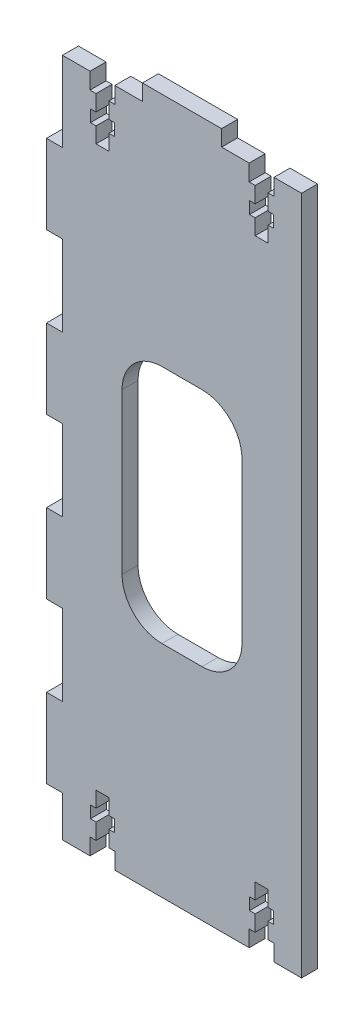
SolidWorks part; units mm, degrees
ref_plane "Front Plane" through (0, 0, 0) normal (0, 0, 1) x (1, 0, 0)
ref_plane "Top Plane" through (0, 0, 0) normal (0, 1, 0) x (1, 0, 0)
ref_plane "Right Plane" through (0, 0, 0) normal (1, 0, 0) x (0, 0, -1)
sketch "Sketch1" plane through (0, 0, 0) normal (0, 0, 1) x (1, 0, 0)
  line L0 (-9.9, 85) -> (-9.9, 89)
  line L1 (-29.9, 85) -> (-9.9, 85)
  line L2 (-29.9, 85) -> (-29.9, -85)
  line L3 (-29.9, -85) -> (29.9, -85)
  line L4 (29.9, 85) -> (29.9, -85)
  line L5 (-29.9, 85) -> (29.9, -85) construction
  line L6 (-29.9, -85) -> (29.9, 85) construction
  line L7 (-9.9, 89) -> (9.9, 89)
  line L8 (9.9, 89) -> (9.9, 85)
  line L9 (9.9, 85) -> (29.9, 85)
  point P0 (0, 0)
  point P8 (0, 89)
  dimension "D1" = 170
  dimension "D2" = 59.8
  dimension "D3" = 19.8
  dimension "D4" = 4
extrude "Boss-Extrude1" add sketch "Sketch1" along normal blind 4
sketch "Sketch3" plane through (0, 0, 0) normal (0, 0, -1) x (-1, 0, 0)
  line L0 (19.9, 85) -> (19.9, 70) construction
  line L1 (9.9, 85) -> (29.9, 85) construction
  line L2 (23, 85) -> (23, 80.9)
  line L3 (23, 80.9) -> (21.5, 80.9)
  line L4 (21.5, 80.9) -> (21.5, 76.9)
  line L5 (21.5, 76.9) -> (22.9, 76.9)
  line L6 (22.9, 76.9) -> (22.9, 73.9)
  line L7 (22.9, 73.9) -> (21.5, 73.9)
  line L8 (21.5, 73.9) -> (21.5, 70)
  line L9 (21.5, 70) -> (18.3, 70)
  line L10 (18.3, 73.9) -> (18.3, 70)
  line L11 (16.9, 73.9) -> (18.3, 73.9)
  line L12 (16.9, 76.9) -> (16.9, 73.9)
  line L13 (18.3, 76.9) -> (16.9, 76.9)
  line L14 (18.3, 80.9) -> (18.3, 76.9)
  line L15 (16.8, 80.9) -> (18.3, 80.9)
  line L16 (16.8, 85) -> (16.8, 80.9)
  line L17 (0, 89) -> (0, -85) construction
  line L18 (-9.9, 89) -> (9.9, 89) construction
  line L19 (29.9, -85) -> (-29.9, -85) construction
  line L20 (-29.9, 0) -> (29.9, 0) construction
  line L21 (-29.9, -85) -> (-29.9, 85) construction
  line L22 (29.9, 85) -> (29.9, -85) construction
  line L23 (-19.9, 85) -> (-19.9, 70) construction
  line L24 (-16.8, 85) -> (-16.8, 80.9)
  line L25 (-16.8, 80.9) -> (-18.3, 80.9)
  line L26 (-18.3, 80.9) -> (-18.3, 76.9)
  line L27 (-18.3, 76.9) -> (-16.9, 76.9)
  line L28 (-16.9, 76.9) -> (-16.9, 73.9)
  line L29 (-16.9, 73.9) -> (-18.3, 73.9)
  line L30 (-18.3, 73.9) -> (-18.3, 70)
  line L31 (-21.5, 70) -> (-18.3, 70)
  line L32 (-21.5, 73.9) -> (-21.5, 70)
  line L33 (-22.9, 73.9) -> (-21.5, 73.9)
  line L34 (-22.9, 76.9) -> (-22.9, 73.9)
  line L35 (-21.5, 76.9) -> (-22.9, 76.9)
  line L36 (-21.5, 80.9) -> (-21.5, 76.9)
  line L37 (-23, 80.9) -> (-21.5, 80.9)
  line L38 (-23, 85) -> (-23, 80.9)
  line L39 (-19.9, -85) -> (-19.9, -70) construction
  line L40 (19.9, -85) -> (19.9, -70) construction
  line L41 (-23, -85) -> (-23, -80.9)
  line L42 (-23, -80.9) -> (-21.5, -80.9)
  line L43 (-21.5, -80.9) -> (-21.5, -76.9)
  line L44 (-21.5, -76.9) -> (-22.9, -76.9)
  line L45 (-22.9, -76.9) -> (-22.9, -73.9)
  line L46 (-22.9, -73.9) -> (-21.5, -73.9)
  line L47 (-21.5, -73.9) -> (-21.5, -70)
  line L48 (-21.5, -70) -> (-18.3, -70)
  line L49 (-18.3, -73.9) -> (-18.3, -70)
  line L50 (-16.9, -73.9) -> (-18.3, -73.9)
  line L51 (-16.9, -76.9) -> (-16.9, -73.9)
  line L52 (-18.3, -76.9) -> (-16.9, -76.9)
  line L53 (-18.3, -80.9) -> (-18.3, -76.9)
  line L54 (-16.8, -80.9) -> (-18.3, -80.9)
  line L55 (-16.8, -85) -> (-16.8, -80.9)
  line L56 (16.8, -85) -> (16.8, -80.9)
  line L57 (16.8, -80.9) -> (18.3, -80.9)
  line L58 (18.3, -80.9) -> (18.3, -76.9)
  line L59 (18.3, -76.9) -> (16.9, -76.9)
  line L60 (16.9, -76.9) -> (16.9, -73.9)
  line L61 (16.9, -73.9) -> (18.3, -73.9)
  line L62 (18.3, -73.9) -> (18.3, -70)
  line L63 (21.5, -70) -> (18.3, -70)
  line L64 (21.5, -73.9) -> (21.5, -70)
  line L65 (22.9, -73.9) -> (21.5, -73.9)
  line L66 (22.9, -76.9) -> (22.9, -73.9)
  line L67 (21.5, -76.9) -> (22.9, -76.9)
  line L68 (21.5, -80.9) -> (21.5, -76.9)
  line L69 (23, -80.9) -> (21.5, -80.9)
  line L70 (23, -85) -> (23, -80.9)
  line L71 (16.8, 85) -> (23, 85)
  line L72 (-23, 85) -> (-16.8, 85)
  line L73 (16.8, -85) -> (23, -85)
  line L74 (-23, -85) -> (-16.8, -85)
  point P6 (21.5, 78.9)
  dimension "D1" = 15
  dimension "D2" = 4.1
  dimension "D3" = 4
  dimension "D4" = 3
  dimension "D5" = 6.2
  dimension "D6" = 3.2
  dimension "D7" = 6
extrude "Cut-Extrude1" cut sketch "Sketch3" against normal through all
sketch "Sketch5" plane through (0, 0, 4) normal (0, 0, 1) x (1, 0, 0)
  line L0 (-29.9, 85) -> (-29.9, -85) construction
  line L1 (-29.9, 65) -> (-33.9, 65)
  line L2 (-29.9, 65) -> (-29.9, 45.2)
  line L3 (-29.9, 45.2) -> (-33.9, 45.2)
  line L4 (-33.9, 65) -> (-33.9, 45.2)
  line L5 (-23, 85) -> (-29.9, 85) construction
  line L6 (-29.9, 25) -> (-33.9, 25)
  line L7 (-29.9, 5.2) -> (-33.9, 5.2)
  line L8 (-33.9, 25) -> (-33.9, 5.2)
  line L9 (-29.9, 25) -> (-29.9, 5.2)
  line L10 (-29.9, -15) -> (-33.9, -15)
  line L11 (-29.9, -34.8) -> (-33.9, -34.8)
  line L12 (-33.9, -15) -> (-33.9, -34.8)
  line L13 (-29.9, -15) -> (-29.9, -34.8)
  line L14 (-29.9, -55) -> (-33.9, -55)
  line L15 (-29.9, -74.8) -> (-33.9, -74.8)
  line L16 (-33.9, -55) -> (-33.9, -74.8)
  line L17 (-29.9, -55) -> (-29.9, -74.8)
  dimension "D1" = 4
  dimension "D2" = 19.8
  dimension "D3" = 20
  dimension "D4" = 4
extrude "Boss-Extrude2" add sketch "Sketch5" against normal up to surface (4 mm away) up to face at (0, 4.8333, 0)
sketch "Sketch6" plane through (0, 0, 4) normal (0, 0, 1) x (1, 0, 0)
  line L1 (-5, 30) -> (5, 30)
  line L2 (-15, 20) -> (-15, -20)
  line L3 (-5, -30) -> (5, -30)
  line L4 (15, 20) -> (15, -20)
  line L5 (-15, 30) -> (15, -30) construction
  line L6 (-15, -30) -> (15, 30) construction
  arc A0 (-15, -20) -> (-5, -30) centre (-5, -20) ccw
  arc A1 (5, -30) -> (15, -20) centre (5, -20) ccw
  arc A2 (5, 30) -> (15, 20) centre (5, 20) cw
  arc A3 (-5, 30) -> (-15, 20) centre (-5, 20) ccw
  point P0 (0, 0)
  point P6 (0, 0)
  dimension "D3" = 10
  dimension "D1" = 30
  dimension "D2" = 60
extrude "Cut-Extrude2" cut sketch "Sketch6" against normal through all
